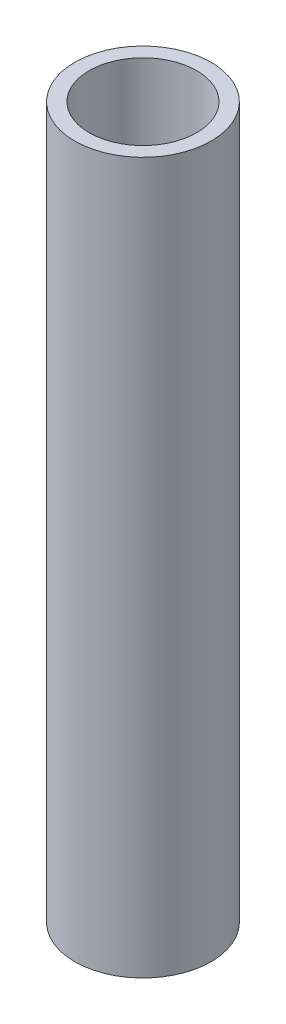
SolidWorks part; units mm, degrees
ref_plane "Ön Düzlem" through (0, 0, 0) normal (0, 0, 1) x (1, 0, 0)
ref_plane "Üst Düzlem" through (0, 0, 0) normal (0, 1, 0) x (1, 0, 0)
ref_plane "Sağ Düzlem" through (0, 0, 0) normal (1, 0, 0) x (0, 0, -1)
sketch "Çizim1" plane through (0, 0, 0) normal (0, 1, 0) x (1, 0, 0)
  circle A0 centre (0, 0) radius 3.55
  circle A1 centre (0, 0) radius 2.8
extrude "Yükseklik-Ekstrüzyon1" add sketch "Çizim1" along normal blind 37
